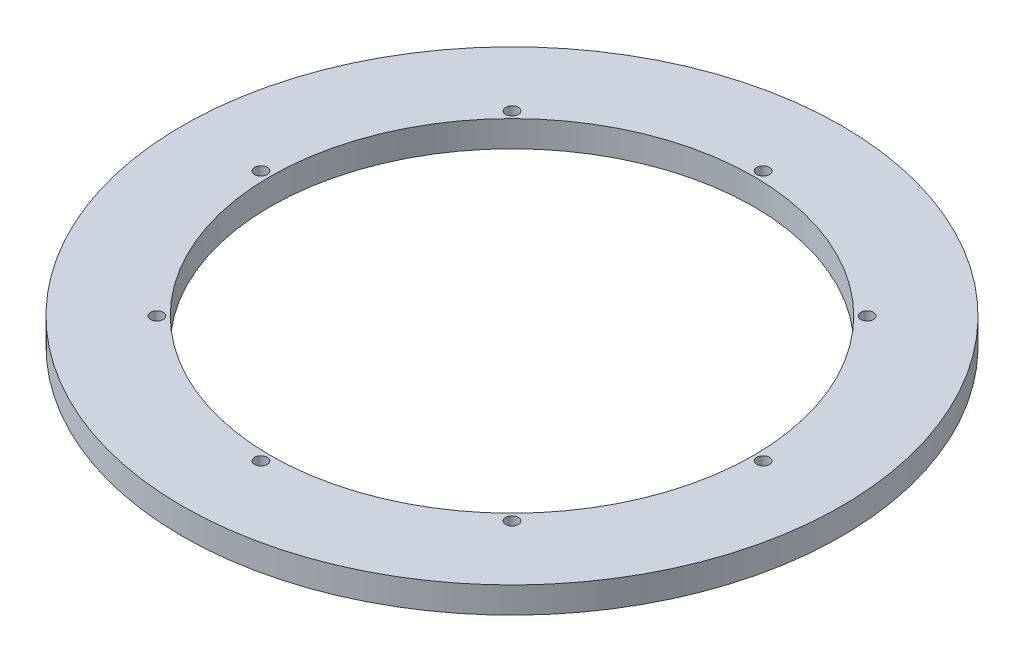
SolidWorks part; units mm, degrees
material "Oak"
ref_plane "Front Plane" through (0, 0, 0) normal (0, 0, 1) x (1, 0, 0)
ref_plane "Top Plane" through (0, 0, 0) normal (0, 1, 0) x (1, 0, 0)
ref_plane "Right Plane" through (0, 0, 0) normal (1, 0, 0) x (0, 0, -1)
sketch "Sketch1" plane through (0, 0, 0) normal (0, 1, 0) x (1, 0, 0)
  line L0 (0, -5938.2077) -> (0, 290972.1766) construction
  line L1 (-5938.2077, 0) -> (290972.1766, 0) construction
  circle A0 centre (0, 0) radius 315
  circle A1 centre (0, 0) radius 231
  circle A2 centre (0, 240) radius 6
  circle A3 centre (169.7056, 169.7056) radius 6
  circle A4 centre (240, 0) radius 6
  circle A5 centre (169.7056, -169.7056) radius 6
  circle A6 centre (0, -240) radius 6
  circle A7 centre (-169.7056, -169.7056) radius 6
  circle A8 centre (-240, 0) radius 6
  circle A9 centre (-169.7056, 169.7056) radius 6
  point P27 (0, 0)
  dimension "D1" = 630
  dimension "D2" = 240
  dimension "D3" = 12
  dimension "D4" = 8
extrude "Boss-Extrude1" add sketch "Sketch1" along normal mid plane 25
